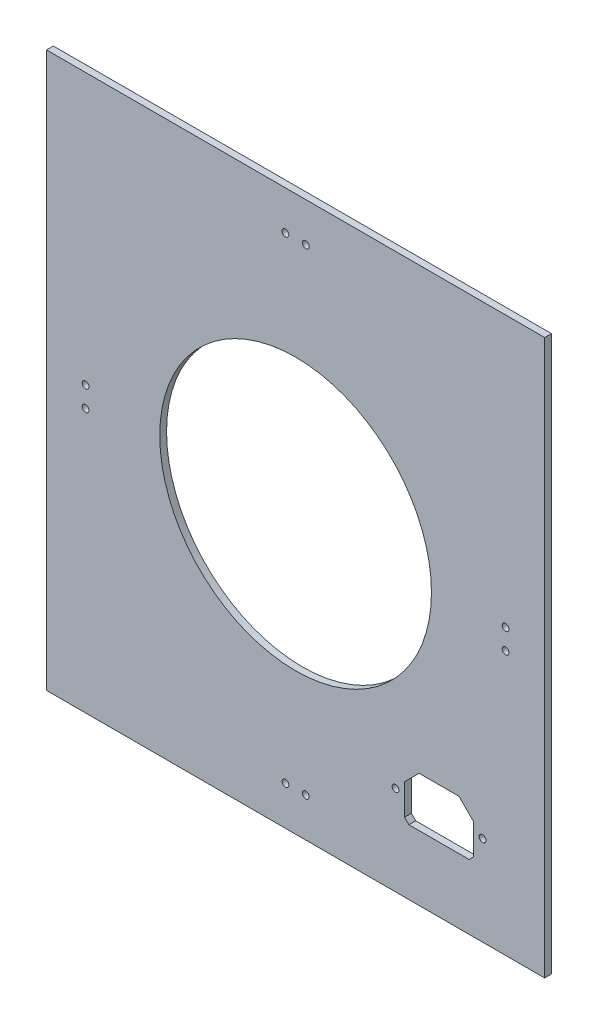
SolidWorks part; units mm, degrees
ref_plane "Front Plane" through (0, 0, 0) normal (0, 0, 1) x (1, 0, 0)
ref_plane "Top Plane" through (0, 0, 0) normal (0, 1, 0) x (1, 0, 0)
ref_plane "Right Plane" through (0, 0, 0) normal (1, 0, 0) x (0, 0, -1)
sketch "Sketch1" plane through (0, 0, 0) normal (0, 0, 1) x (1, 0, 0)
  line L1 (-210, -117.958) -> (0, -117.958)
  line L2 (-210, -117.958) -> (-210, 127.042)
  line L3 (-210, 127.042) -> (0, 127.042)
  line L4 (0, -117.958) -> (0, 127.042)
  line L5 (-210, -117.958) -> (0, 127.042) construction
  line L6 (-210, 127.042) -> (0, -117.958) construction
  point P0 (-105, 4.542)
  dimension "D1" = 210
  dimension "D2" = 245
extrude "Boss-Extrude1" add sketch "Sketch1" along normal blind 3
sketch "Sketch2" plane through (0, 0, 3) normal (0, 0, 1) x (1, 0, 0)
  line L0 (-105, 127.042) -> (-105, -117.958) construction
  line L4 (0, -117.958) -> (0, 127.042)
  line L5 (0, 127.042) -> (-210, 127.042)
  line L6 (-210, 127.042) -> (-210, -117.958)
  line L7 (-210, -117.958) -> (0, -117.958)
  line L8 (0, -117.958) -> (0, 127.042)
  line L9 (0, 127.042) -> (-210, 127.042)
  line L10 (-210, 127.042) -> (-210, -117.958)
  line L11 (-210, -117.958) -> (0, -117.958)
  circle A0 centre (-105, 4.542) radius 60
  dimension "D1" = 0
extrude "Cut-Extrude1" cut sketch "Sketch2" against normal blind 3 contours L0 A0 | A0 L0
sketch "Sketch3" plane through (0, 0, 3) normal (0, 0, 1) x (1, 0, 0)
  line L0 (-41.653, 17.7007) -> (-41.653, -101.7011) construction
  line L1 (-28.653, -88.602) -> (-54.653, -88.602)
  line L2 (-54.653, -88.602) -> (-56.1634, -87.0916)
  line L3 (-56.1634, -87.0916) -> (-56.1634, -74.0916)
  line L4 (0, -117.958) -> (0, 127.042)
  line L5 (0, 127.042) -> (-210, 127.042)
  line L6 (-210, 127.042) -> (-210, -117.958)
  line L7 (-210, -117.958) -> (0, -117.958)
  line L8 (0, -117.958) -> (0, 127.042)
  line L9 (0, 127.042) -> (-210, 127.042)
  line L10 (-210, 127.042) -> (-210, -117.958)
  line L11 (-210, -117.958) -> (0, -117.958)
  line L12 (-56.1634, -74.0916) -> (-50.153, -68.0812)
  line L13 (-50.153, -68.0812) -> (-33.153, -68.0812)
  line L14 (-27.1426, -74.0916) -> (-33.153, -68.0812)
  line L15 (-27.1426, -87.0916) -> (-27.1426, -74.0916)
  line L16 (-28.653, -88.602) -> (-27.1426, -87.0916)
  line L17 (-28.3631, -89.302) -> (-54.943, -89.302)
  line L18 (-54.943, -89.302) -> (-56.8634, -87.3816)
  line L19 (-56.8634, -87.3816) -> (-56.8634, -73.8017)
  line L20 (-56.8634, -73.8017) -> (-50.443, -67.3812)
  line L21 (-50.443, -67.3812) -> (-32.8631, -67.3812)
  line L22 (-26.4426, -73.8017) -> (-32.8631, -67.3812)
  line L23 (-26.4426, -87.3816) -> (-26.4426, -73.8017)
  line L24 (-28.3631, -89.302) -> (-26.4426, -87.3816)
  point P14 (-41.653, -68.0812)
  point P17 (-41.653, -88.602)
  dimension "D2" = 13
  dimension "D3" = 8.5
  dimension "D4" = 8.5
  dimension "D5" = 13
  dimension "D1" = 0
  dimension "D6" = 0.7
extrude "Cut-Extrude2" cut sketch "Sketch3" against normal blind 3 contours L0 L13 L12 L3 L2 L1 | L0 L21 L20 L19 L18 L17 L1 L2 L3 L12 L13 | L13 L0 L1 L16 L15 L14 | L21 L0 L13 L14 L15 L16 L1 L17 L24 L23 L22
sketch "Sketch4" plane through (0, 0, 3) normal (0, 0, 1) x (1, 0, 0)
  line L0 (-56.8634, -87.3816) -> (-56.8634, -73.8017) construction
  line L1 (-56.8634, -87.3816) -> (-56.8634, -73.8017)
  line L2 (-26.4426, -87.3816) -> (-26.4426, -73.8017) construction
  line L3 (-26.4426, -87.3816) -> (-26.4426, -73.8017)
  line L4 (-60.8634, -87.3816) -> (-60.8634, -73.8017)
  line L5 (-22.4426, -87.3816) -> (-22.4426, -73.8017)
  line L6 (-41.653, -67.3812) -> (-41.653, -89.302) construction
  line L7 (-50.443, -67.3812) -> (-32.8631, -67.3812) construction
  line L8 (-28.3631, -89.302) -> (-54.943, -89.302) construction
  line L9 (-41.653, -89.302) -> (-41.653, -78.3416) construction
  line L10 (-41.653, -78.3416) -> (-11.6555, -78.3416) construction
  circle A0 centre (-60.8634, -78.3416) radius 1.5
  circle A1 centre (-22.4426, -78.3416) radius 1.5
  dimension "D3" = 3
  dimension "D1" = 4
  dimension "D2" = 4
extrude "Cut-Extrude3" cut sketch "Sketch4" against normal through all contours L4 A0 | L4 A0 | L5 A1 | L5 A1
sketch "Sketch5" plane through (0, 0, 0) normal (1, 0, 0) x (0, 0, -1)
  line L4 (0, -117.958) -> (0, 127.042)
  line L5 (0, 127.042) -> (-3, 127.042)
  line L6 (-3, 127.042) -> (-3, -117.958)
  line L7 (-3, -117.958) -> (0, -117.958)
  line L8 (0, -117.958) -> (0, 127.042)
  line L9 (0, 127.042) -> (-3, 127.042)
  line L10 (-3, 127.042) -> (-3, -117.958)
  line L11 (-3, -117.958) -> (0, -117.958)
  dimension "D1" = 0
extrude "Boss-Extrude2" add sketch "Sketch5" along normal blind 5
sketch "Sketch6" plane through (-210, 0, 0) normal (-1, 0, 0) x (0, 0, 1)
  line L4 (0, 127.042) -> (0, -117.958)
  line L5 (0, -117.958) -> (3, -117.958)
  line L6 (3, -117.958) -> (3, 127.042)
  line L7 (3, 127.042) -> (0, 127.042)
  line L8 (0, 127.042) -> (0, -117.958)
  line L9 (0, -117.958) -> (3, -117.958)
  line L10 (3, -117.958) -> (3, 127.042)
  line L11 (3, 127.042) -> (0, 127.042)
  dimension "D1" = 0
extrude "Boss-Extrude3" add sketch "Sketch6" along normal blind 5
sketch "Sketch7" plane through (0, 0, 0) normal (0, 0, -1) x (-1, 0, 0)
  line L1 (-5, -117.958) -> (-5, 127.042)
  line L4 (215, 127.042) -> (-5, 127.042)
  line L5 (-5, 127.042) -> (-5, -117.958)
  line L6 (-5, -117.958) -> (215, -117.958)
  line L7 (215, -117.958) -> (215, 127.042)
  line L8 (215, 127.042) -> (-5, 127.042)
  line L9 (-5, 127.042) -> (-5, -117.958)
  line L10 (-5, -117.958) -> (215, -117.958)
  line L11 (215, -117.958) -> (215, 127.042)
  line L12 (105, 127.042) -> (105, -270.7576) construction
  line L13 (12.253, 7.527) -> (-5, 7.527)
  line L14 (12.253, 7.527) -> (12.253, -1.473)
  line L15 (12.253, 3.027) -> (-5, 3.027)
  line L16 (109.5, 109.789) -> (109.5, 127.042)
  line L17 (50.443, -67.3812) -> (32.8631, -67.3812)
  line L18 (26.4426, -73.8017) -> (32.8631, -67.3812)
  line L19 (26.4426, -87.3816) -> (26.4426, -73.8017)
  line L20 (28.3631, -89.302) -> (54.943, -89.302)
  line L21 (56.8634, -73.8017) -> (50.443, -67.3812)
  line L22 (215, 127.042) -> (215, -117.958)
  line L23 (-5, 127.042) -> (215, 127.042)
  line L24 (215, -117.958) -> (-5, -117.958)
  line L25 (105, 109.789) -> (105, 127.042)
  line L26 (109.5, 109.789) -> (100.5, 109.789)
  line L27 (215, 4.542) -> (298.5393, 4.542)
  line L28 (109.5, -100.7051) -> (100.5, -100.7051)
  line L29 (105, -100.7051) -> (105, -117.958)
  line L30 (109.5, -100.7051) -> (109.5, -117.958)
  circle A4 centre (197.747, -1.473) radius 1.5
  circle A5 centre (197.747, 7.527) radius 1.5
  circle A6 centre (12.253, -1.473) radius 1.5
  circle A7 centre (12.253, 7.527) radius 1.5
  circle A8 centre (100.5, 109.789) radius 1.5
  circle A9 centre (109.5, 109.789) radius 1.5
  circle A10 centre (109.5, -100.7051) radius 1.5
  circle A11 centre (100.5, -100.7051) radius 1.5
  dimension "D1" = 0
extrude "Cut-Extrude4" cut sketch "Sketch7" against normal blind 10
